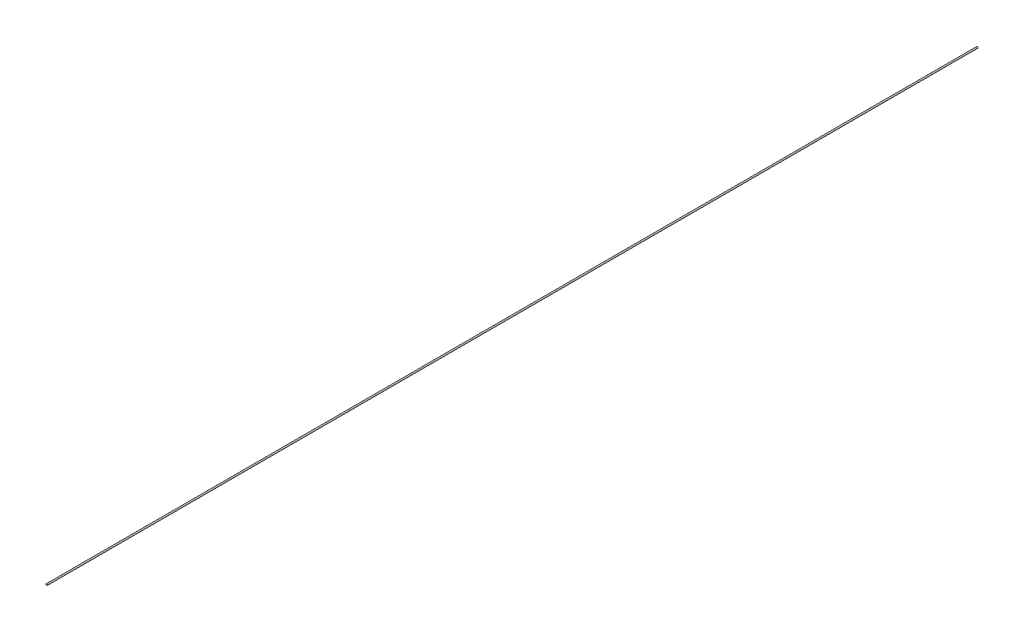
SolidWorks part; units mm, degrees
ref_plane "Front Plane" through (0, 0, 0) normal (0, 0, 1) x (1, 0, 0)
ref_plane "Top Plane" through (0, 0, 0) normal (0, 1, 0) x (1, 0, 0)
ref_plane "Right Plane" through (0, 0, 0) normal (1, 0, 0) x (0, 0, -1)
sketch "Sketch1" plane through (0, 0, 0) normal (0, 0, 1) x (1, 0, 0)
  circle A0 centre (0, 0) radius 0.1
  dimension "D1" = 0.2
extrude "Boss-Extrude1" add sketch "Sketch1" along normal blind 125
